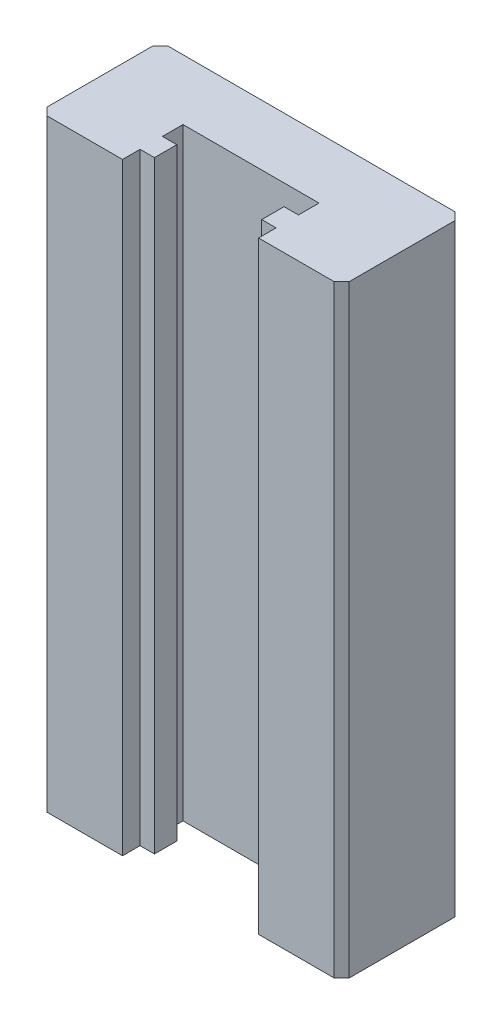
SolidWorks part; units mm, degrees
material "AISI 304"
ref_plane "前视基准面" through (0, 0, 0) normal (0, 0, 1) x (1, 0, 0)
ref_plane "上视基准面" through (0, 0, 0) normal (0, 1, 0) x (1, 0, 0)
ref_plane "右视基准面" through (0, 0, 0) normal (1, 0, 0) x (0, 0, -1)
other "Configuration Table"
sketch "草图1" plane through (0, 0, 0) normal (0, 1, 0) x (1, 0, 0)
  line L0 (0, 0) -> (0, -7.872) construction
  line L1 (-10, -4) -> (10, -4)
  line L2 (-10, -4) -> (-10, 4)
  line L3 (-10, 4) -> (10, 4)
  line L4 (10, -4) -> (10, 4)
  line L5 (-10, -4) -> (10, 4) construction
  line L6 (-10, 4) -> (10, -4) construction
  line L7 (-12.6786, 0) -> (12.6786, 0) construction
  line L8 (-4.5, -4) -> (-4.5, -2.84)
  line L9 (-4.5, -2.84) -> (-3.55, -2.84)
  line L10 (-3.55, -2.84) -> (-3.55, -1.36)
  line L11 (-3.55, -1.36) -> (-4.5, -1.36)
  line L12 (-4.5, -1.36) -> (-4.5, 0)
  line L13 (-4.5, 0) -> (4.5, 0)
  line L14 (-4.5, -4) -> (0, -4)
  line L15 (4.5, -4) -> (4.5, -2.84)
  line L16 (4.5, -2.84) -> (3.55, -2.84)
  line L17 (3.55, -2.84) -> (3.55, -1.36)
  line L18 (3.55, -1.36) -> (4.5, -1.36)
  line L19 (4.5, -1.36) -> (4.5, 0)
  point P0 (0, 0)
  point P11 (0, 0)
  dimension "D1" = 20
  dimension "D2" = 8
  dimension "D3" = 1.36
  dimension "D4" = 1.48
  dimension "D5" = 0.95
  dimension "D6" = 4.5
  dimension "D7" = 0.95
extrude "凸台-拉伸1" add sketch "草图1" along normal blind 39.9 contours L19 L18 L17 L16 L15 L1 L4 L3 L2 L8 L9 L10 L11 L12 L13
sketch "草图2" plane through (0, 0, -4) normal (0, 0, -1) x (-1, 0, 0)
  line L0 (0, 0) -> (0, 39.9) construction
  line L1 (10, 0) -> (-10, 0) construction
  line L2 (10, 39.9) -> (-10, 39.9) construction
  line L3 (0, 19.95) -> (10, 19.95) construction
  line L4 (10, 39.9) -> (10, 0) construction
  circle A0 centre (7.5, 27.95) radius 1.5
  circle A1 centre (-7.5, 27.95) radius 1.5
  circle A2 centre (7.5, 11.95) radius 1.5
  circle A3 centre (-7.5, 11.95) radius 1.5
  dimension "D1" = 3
  dimension "D2" = 16
  dimension "D3" = 15
extrude "切除-拉伸1" cut sketch "草图2" against normal blind 3
chamfer "倒角1" distance 0.5 angle 45 4 edges at (-10, 19.95, 4) (10, 19.95, 4) (10, 19.95, -4) (-10, 19.95, -4)
